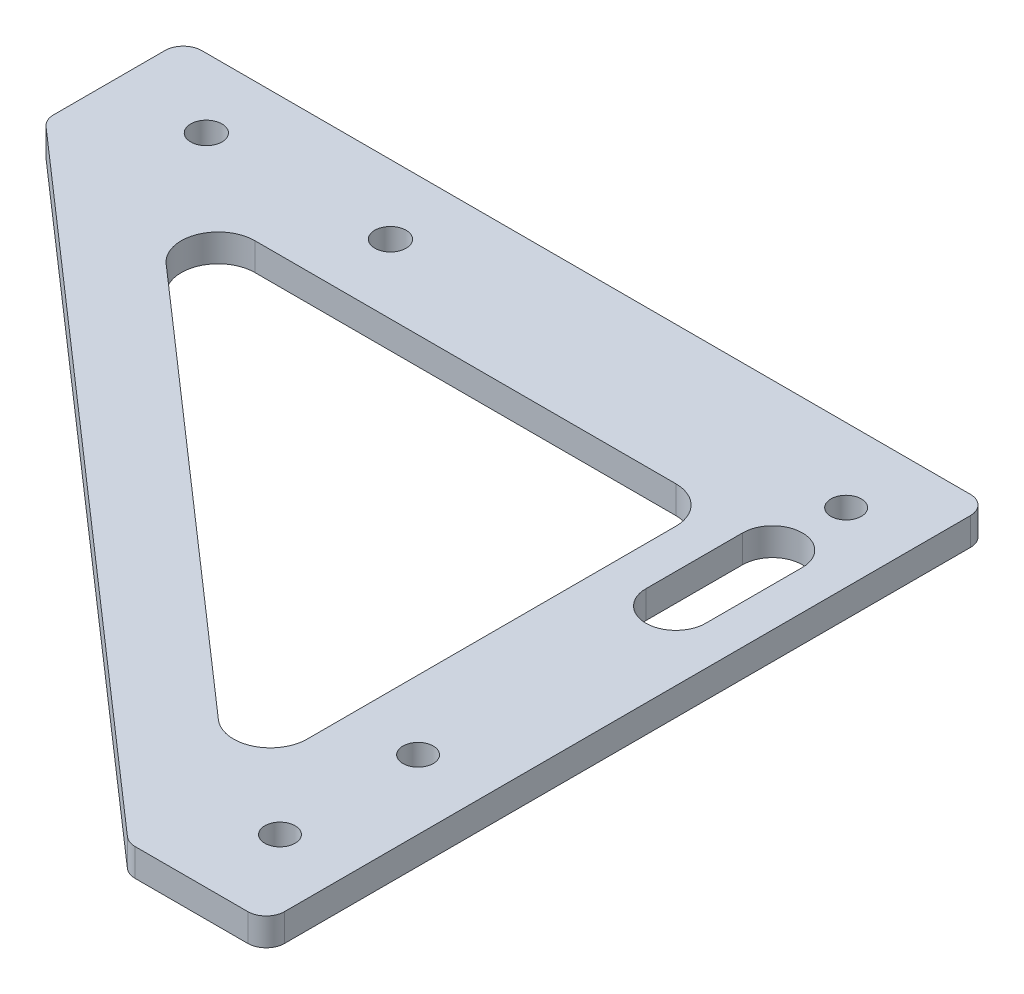
SolidWorks part; units mm, degrees
ref_plane "前视基准面" through (0, 0, 0) normal (0, 0, 1) x (1, 0, 0)
ref_plane "上视基准面" through (0, 0, 0) normal (0, 1, 0) x (1, 0, 0)
ref_plane "右视基准面" through (0, 0, 0) normal (1, 0, 0) x (0, 0, -1)
sketch "草图1" plane through (0, 0, 0) normal (0, 1, 0) x (1, 0, 0)
  line L0 (0, 0) -> (0, 10.5) construction
  line L1 (-3.25, 0) -> (-3.25, 10.5)
  line L2 (3.25, 0) -> (3.25, 10.5)
  line L3 (0, 29.8626) -> (0, -39.1312) construction
  line L4 (-80, 11.5) -> (-7.5, -52)
  line L5 (7.5, -52) -> (-7.5, -52)
  line L6 (7.5, -52) -> (7.5, 26.5)
  line L7 (7.5, 26.5) -> (-7.5, 26.5)
  line L8 (-7.5, -32.5445) -> (-7.5, 7.5)
  line L9 (-7.5, 26.5) -> (-80, 26.5)
  line L11 (-11.5, 11.5) -> (-57.2201, 11.5)
  line L12 (-80, 26.5) -> (-80, 11.5)
  line L13 (-59.8556, 4.491) -> (-14.1355, -35.5535)
  arc A0 (-3.25, 0) -> (3.25, 0) centre (0, 0) ccw
  arc A1 (3.25, 10.5) -> (-3.25, 10.5) centre (0, 10.5) ccw
  circle A2 centre (0, 18.5) radius 1.65
  circle A3 centre (0, -28) radius 1.65
  circle A4 centre (0, -43) radius 1.65
  circle A5 centre (-70, 19) radius 1.7
  circle A6 centre (-50, 19) radius 1.7
  circle A7 centre (0, 10.5) radius 30 construction
  arc A8 (-57.2201, 11.5) -> (-59.8556, 4.491) centre (-57.2201, 7.5) ccw
  arc A9 (-7.5, 7.5) -> (-11.5, 11.5) centre (-11.5, 7.5) ccw
  arc A10 (-14.1355, -35.5535) -> (-7.5, -32.5445) centre (-11.5, -32.5445) ccw
  point P3 (0, 5.25)
  dimension "D2" = 3.25
  dimension "D3" = 3.3
  dimension "D4" = 8
  dimension "D5" = 3.3
  dimension "D7" = 3.3
  dimension "D8" = 15
  dimension "D15" = 3.4
  dimension "D16" = 20
  dimension "D17" = 10
  dimension "D18" = 60
  dimension "D21" = 7.5
  dimension "D22" = 7.5
  dimension "D23" = 8
  dimension "D1" = 10.5
  dimension "D6" = 28
  dimension "D9" = 15
  dimension "D10" = 7.5
  dimension "D11" = 9
  dimension "D12" = 8
  dimension "D13" = 15
  dimension "D14" = 80
  dimension "D19" = 8
  dimension "D20" = 15
extrude "凸台-拉伸1" add sketch "草图1" along normal blind 3
fillet "圆角1" radius 2 5 edges at (-80, 1.5, -26.5) (-80, 1.5, -11.5) (-7.5, 1.5, 52) (7.5, 1.5, 52) (7.5, 1.5, -26.5)
